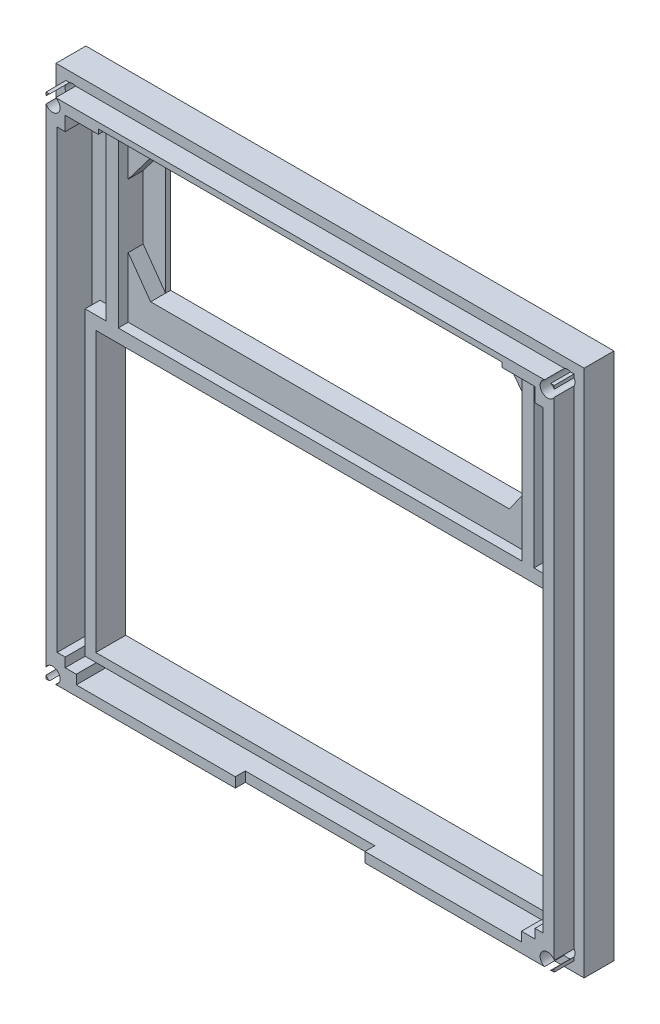
SolidWorks part; units mm, degrees
ref_plane "前视基准面" through (0, 0, 0) normal (0, 0, 1) x (1, 0, 0)
ref_plane "上视基准面" through (0, 0, 0) normal (0, 1, 0) x (1, 0, 0)
ref_plane "右视基准面" through (0, 0, 0) normal (1, 0, 0) x (0, 0, -1)
sketch "草图1" plane through (0, 0, 0) normal (0, 0, 1) x (1, 0, 0)
  line L0 (2, 104) -> (104, 104) construction
  line L1 (0, 0) -> (106, 0)
  line L2 (0, 0) -> (0, 106)
  line L3 (0, 106) -> (106, 106)
  line L4 (106, 0) -> (106, 106)
  line L5 (104, 2) -> (104, 104) construction
  line L6 (2, 2) -> (104, 2) construction
  line L7 (2, 2) -> (2, 104) construction
  line L8 (53, 106) -> (53, 0) construction
  line L9 (0, 53) -> (106, 53) construction
  line L11 (17, 97.0371) -> (89, 97.0371)
  line L12 (17, 97.0371) -> (17, 72.0371)
  line L13 (17, 72.0371) -> (89, 72.0371)
  line L14 (89, 97.0371) -> (89, 72.0371)
  line L15 (8, 63.5755) -> (98, 63.5755)
  line L16 (8, 63.5755) -> (8, 7.5755)
  line L17 (8, 7.5755) -> (98, 7.5755)
  line L18 (98, 63.5755) -> (98, 7.5755)
  circle A0 centre (3.3245, 102.6364) radius 1.5
  circle A1 centre (102.6755, 102.6364) radius 1.5
  circle A2 centre (102.6755, 3.3636) radius 1.5
  circle A3 centre (3.3245, 3.3636) radius 1.5
  dimension "D4" = 3
  dimension "D1" = 106
  dimension "D2" = 106
  dimension "D3" = 2
  dimension "D5" = 72
  dimension "D6" = 25
  dimension "D7" = 90
  dimension "D8" = 56
extrude "凸台-拉伸1" add sketch "草图1" along normal blind 10
sketch "草图2" plane through (0, 0, 10) normal (0, 0, 1) x (1, 0, 0)
  line L0 (2, 104) -> (104, 104)
  line L1 (0, 106) -> (106, 106)
  line L2 (0, 106) -> (0, 0)
  line L3 (0, 0) -> (106, 0)
  line L4 (106, 106) -> (106, 0)
  line L5 (104, 104) -> (104, 2)
  line L6 (2, 2) -> (104, 2)
  line L7 (2, 104) -> (2, 2)
  dimension "D1" = 2
extrude "切除-拉伸1" cut sketch "草图2" against normal blind 4
sketch "草图3" plane through (0, 0, 10) normal (0, 0, 1) x (1, 0, 0)
  line L0 (53, 104) -> (53, 2) construction
  line L1 (12.5, 102.8371) -> (93.5, 102.8371)
  line L2 (12.5, 102.8371) -> (12.5, 66.2371)
  line L3 (12.5, 66.2371) -> (93.5, 66.2371)
  line L4 (93.5, 102.8371) -> (93.5, 66.2371)
  line L5 (102.0506, 104) -> (3.9494, 104) construction
  line L6 (3.9494, 2) -> (102.0506, 2) construction
  line L7 (2, 53) -> (104, 53) construction
  line L8 (2, 101.9323) -> (2, 4.0677) construction
  line L9 (104, 4.0677) -> (104, 101.9323) construction
  line L10 (17, 84.5371) -> (89, 84.5371) construction
  line L11 (17, 97.0371) -> (17, 72.0371) construction
  line L12 (89, 72.0371) -> (89, 97.0371) construction
  dimension "D1" = 81
  dimension "D2" = 36.6
extrude "切除-拉伸2" cut sketch "草图3" against normal blind 6
sketch "草图4" plane through (0, 0, 10) normal (0, 0, 1) x (1, 0, 0)
  line L0 (53, 104) -> (53, 2) construction
  line L1 (4.2385, 99.0353) -> (5.8495, 99.0353)
  line L2 (4.2385, 99.0353) -> (4.2385, 7.7082)
  line L3 (4.2385, 7.7082) -> (5.8495, 7.7082)
  line L4 (5.8495, 66.2371) -> (5.8495, 7.7082)
  line L5 (10.0626, 66.2371) -> (5.8495, 66.2371)
  line L6 (10.0626, 66.2371) -> (10.0626, 101.8854)
  line L7 (10.0626, 101.8854) -> (5.8495, 101.8854)
  line L8 (5.8495, 99.0353) -> (5.8495, 101.8854)
  line L9 (102.0506, 104) -> (3.9494, 104) construction
  line L10 (3.9494, 2) -> (102.0506, 2) construction
  line L11 (95.9374, 66.2371) -> (100.1505, 66.2371)
  line L12 (100.1505, 66.2371) -> (100.1505, 7.7082)
  line L13 (101.7615, 7.7082) -> (100.1505, 7.7082)
  line L14 (101.7615, 99.0353) -> (101.7615, 7.7082)
  line L15 (101.7615, 99.0353) -> (100.1505, 99.0353)
  line L16 (100.1505, 99.0353) -> (100.1505, 101.8854)
  line L17 (95.9374, 101.8854) -> (100.1505, 101.8854)
  line L18 (95.9374, 66.2371) -> (95.9374, 101.8854)
  line L20 (8.08, 5.8495) -> (97.4244, 5.8495)
  line L21 (8.08, 5.8495) -> (8.08, 3.9907)
  line L22 (8.08, 3.9907) -> (97.4244, 3.9907)
  line L23 (97.4244, 5.8495) -> (97.4244, 3.9907)
extrude "切除-拉伸3" cut sketch "草图4" against normal blind 7
sketch "草图5" plane through (0, 0, 10) normal (0, 0, 1) x (1, 0, 0)
  line L0 (10.0626, 101.8854) -> (5.8495, 101.8854) construction
  line L1 (7.9561, 101.8854) -> (98.0439, 101.8854)
  line L2 (7.9561, 101.8854) -> (7.9561, 66.2371)
  line L4 (98.0439, 101.8854) -> (98.0439, 66.2371)
  line L5 (95.9374, 66.2371) -> (100.1505, 66.2371) construction
  line L6 (98.0439, 66.2371) -> (100.1505, 66.2371)
  line L7 (5.8495, 66.2371) -> (7.9561, 66.2371)
  line L8 (5.8495, 66.2371) -> (5.8495, 5.8495)
  line L9 (5.8495, 5.8495) -> (100.1505, 5.8495)
  line L10 (100.1505, 66.2371) -> (100.1505, 5.8495)
extrude "切除-拉伸4" cut sketch "草图5" against normal blind 4
sketch "草图6" plane through (0, 0, 4) normal (0, 0, 1) x (1, 0, 0)
  line L0 (17, 97.0371) -> (12.5, 91.1046)
  line L1 (12.5, 102.8371) -> (12.5, 66.2371) construction
  line L2 (12.5, 91.1046) -> (12.5, 78.3411)
  line L3 (12.5, 66.2371) -> (12.5, 101.8854) construction
  line L4 (12.5, 78.3411) -> (17, 72.0371)
  line L5 (17, 72.0371) -> (17, 97.0371)
  line L6 (53, 97.0371) -> (53, 72.0371) construction
  line L7 (89, 97.0371) -> (17, 97.0371) construction
  line L8 (17, 72.0371) -> (89, 72.0371) construction
  line L9 (89, 72.0371) -> (89, 97.0371)
  line L10 (93.5, 78.3411) -> (89, 72.0371)
  line L11 (93.5, 91.1046) -> (93.5, 78.3411)
  line L12 (89, 97.0371) -> (93.5, 91.1046)
extrude "切除-拉伸5" cut sketch "草图6" against normal blind 3
sketch "草图8" plane through (0, 0, 10) normal (0, 0, 1) x (1, 0, 0)
  line L0 (0, 106) -> (0, 0) construction
  line L1 (40, 11.9988) -> (66, 11.9988)
  line L2 (40, 11.9988) -> (40, -5.4914)
  line L3 (40, -5.4914) -> (66, -5.4914)
  line L4 (66, 11.9988) -> (66, -5.4914)
  line L5 (106, 0) -> (106, 106) construction
  dimension "D1" = 40
  dimension "D2" = 40
extrude "切除-拉伸6" cut sketch "草图8" against normal blind 2
